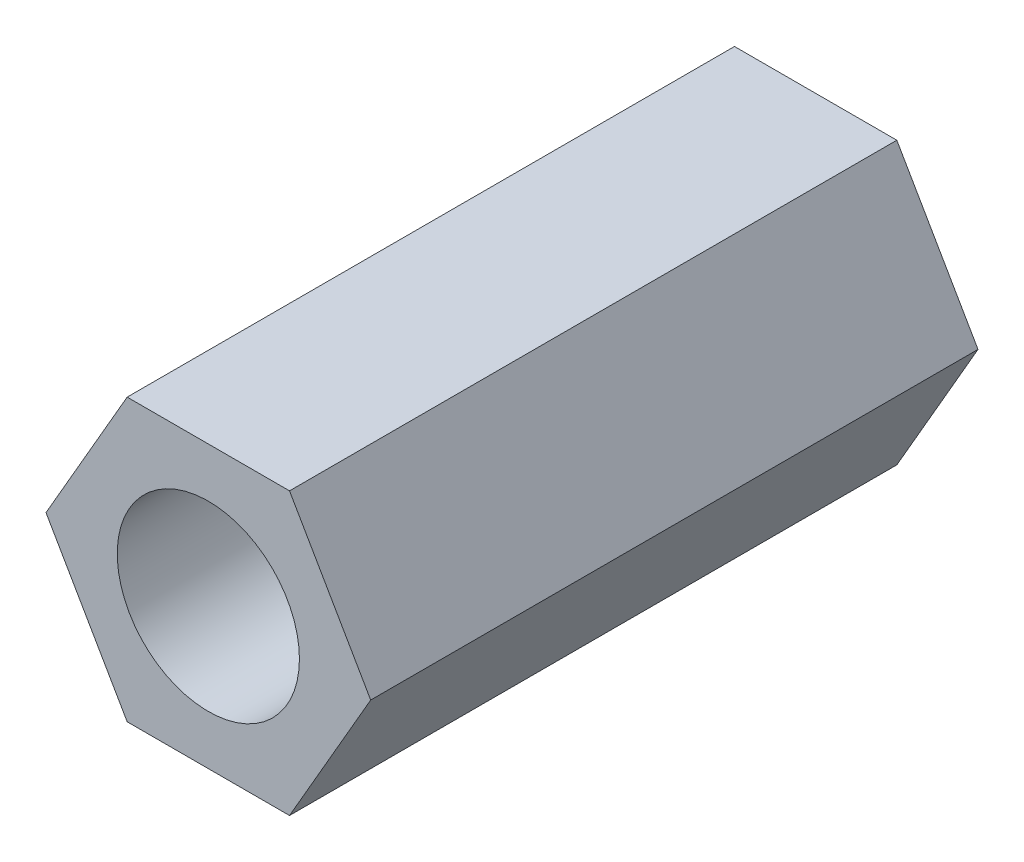
SolidWorks part; units mm, degrees
ref_plane "Front Plane" through (0, 0, 0) normal (0, 0, 1) x (1, 0, 0)
ref_plane "Top Plane" through (0, 0, 0) normal (0, 1, 0) x (1, 0, 0)
ref_plane "Right Plane" through (0, 0, 0) normal (1, 0, 0) x (0, 0, -1)
sketch "Sketch1" plane through (0, 0, 0) normal (0, 0, 1) x (1, 0, 0)
  line L1 (2.6731, 0) -> (1.3366, 2.315)
  line L2 (1.3366, 2.315) -> (-1.3366, 2.315)
  line L3 (-1.3366, 2.315) -> (-2.6731, 0)
  line L4 (-2.6731, 0) -> (-1.3366, -2.315)
  line L5 (-1.3366, -2.315) -> (1.3366, -2.315)
  line L6 (1.3366, -2.315) -> (2.6731, 0)
  circle A0 centre (0, 0) radius 2.315 construction
  circle A2 centre (0, 0) radius 1.5
  dimension "D1" = 3
  dimension "D2" = 4.63
extrude "Boss-Extrude1" add sketch "Sketch1" along normal blind 10
